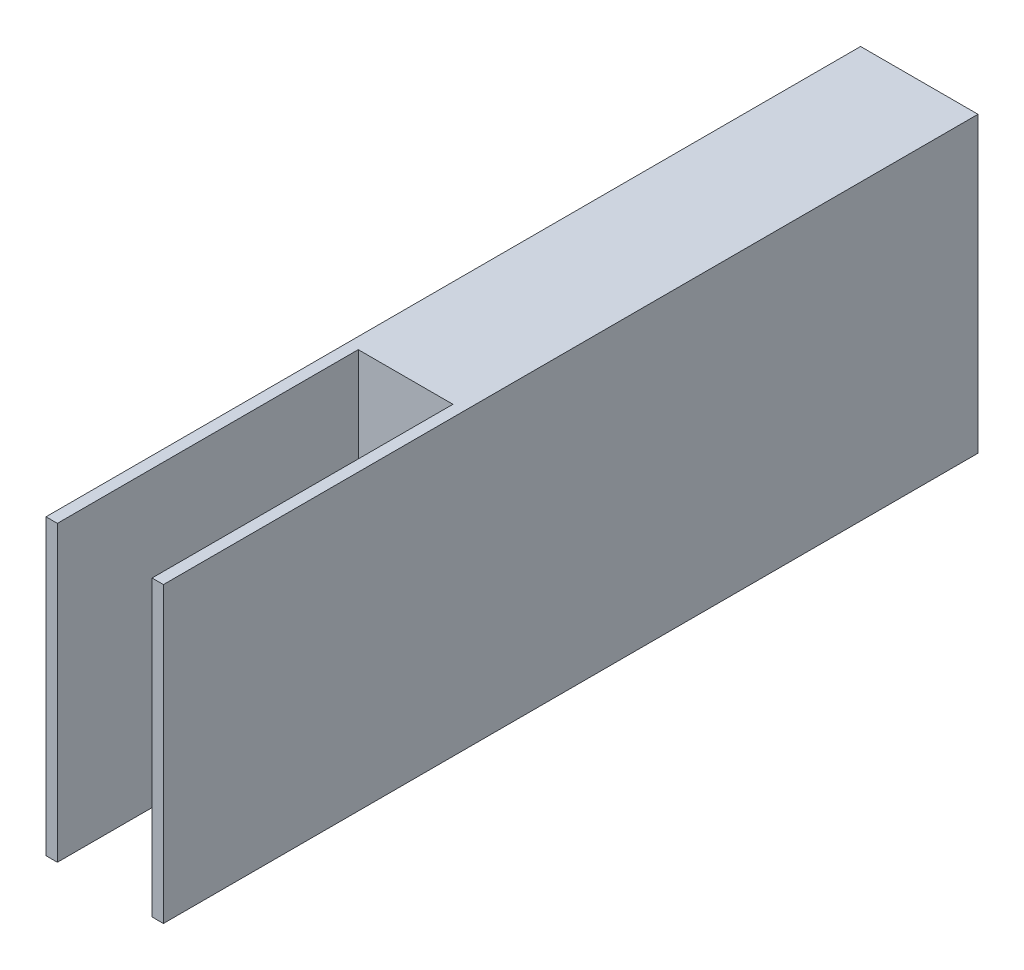
SolidWorks part; units mm, degrees
ref_plane "Plan de face" through (0, 0, 0) normal (0, 0, 1) x (1, 0, 0)
ref_plane "Plan de dessus" through (0, 0, 0) normal (0, 1, 0) x (1, 0, 0)
ref_plane "Plan de droite" through (0, 0, 0) normal (1, 0, 0) x (0, 0, -1)
sketch "Esquisse1" plane through (0, 0, 0) normal (0, 0, 1) x (1, 0, 0)
  line L1 (-4.3694, 6.4826) -> (3.6306, 6.4826)
  line L2 (-4.3694, 6.4826) -> (-4.3694, -13.5174)
  line L3 (-4.3694, -13.5174) -> (3.6306, -13.5174)
  line L4 (3.6306, 6.4826) -> (3.6306, -13.5174)
  dimension "D1" = 8
  dimension "D2" = 20
extrude "Boss.-Extru.1" add sketch "Esquisse1" along normal blind 35
sketch "Esquisse3" plane through (0, 0, 35) normal (0, 0, 1) x (1, 0, 0)
  line L0 (-4.3694, 6.4826) -> (-4.3694, -13.5174) construction
  line L1 (-4.3694, 6.4826) -> (-3.5944, 6.4826)
  line L2 (-4.3694, 6.4826) -> (-4.3694, -13.5174)
  line L3 (-4.3694, -13.5174) -> (-3.5944, -13.5174)
  line L4 (-3.5944, 6.4826) -> (-3.5944, -13.5174)
  line L5 (-4.3694, -13.5174) -> (3.6306, -13.5174) construction
  line L6 (3.6306, 6.4826) -> (-4.3694, 6.4826) construction
  line L7 (3.6306, -13.5174) -> (2.8556, -13.5174)
  line L8 (3.6306, -13.5174) -> (3.6306, 6.4826)
  line L9 (3.6306, 6.4826) -> (2.8556, 6.4826)
  line L10 (2.8556, -13.5174) -> (2.8556, 6.4826)
  point P15 (-1.1656, 6.359)
  point P16 (-1.1717, 6.4826)
  dimension "D1" = 0.775
  dimension "D2" = 6.45
  dimension "D3" = 0.775
extrude "Boss.-Extru.2" add sketch "Esquisse3" along normal blind 20.5
